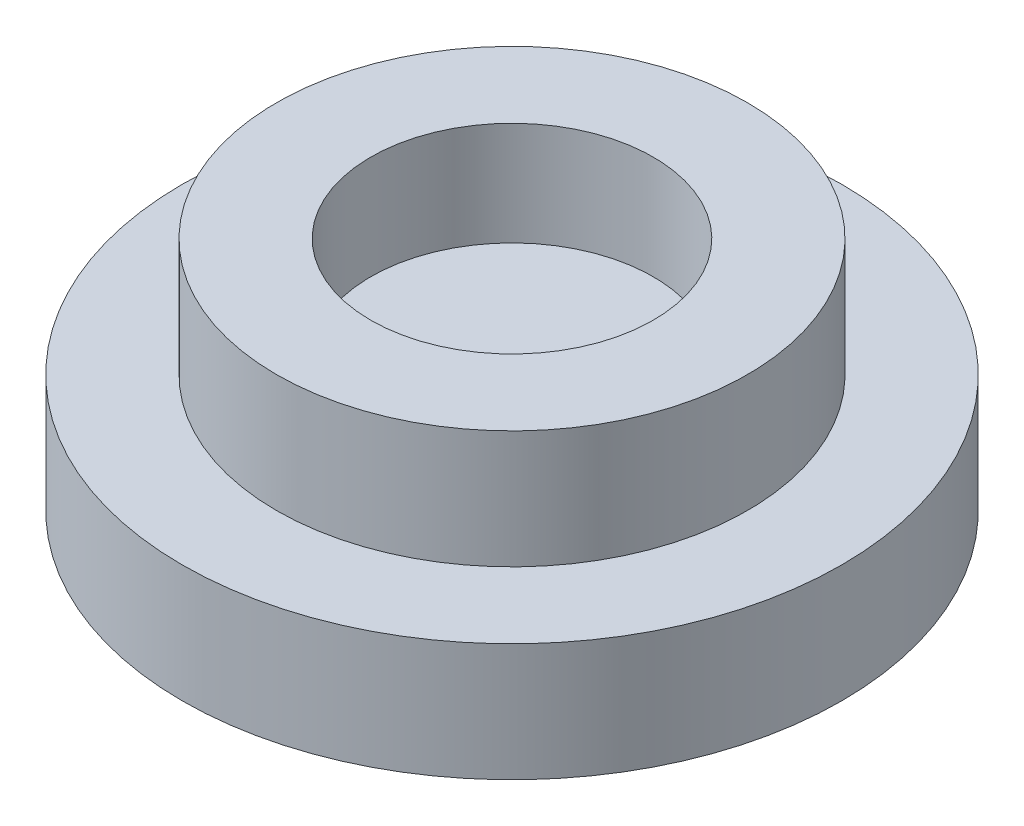
SolidWorks part; units mm, degrees
ref_plane "Front Plane" through (0, 0, 0) normal (0, 0, 1) x (1, 0, 0)
ref_plane "Top Plane" through (0, 0, 0) normal (0, 1, 0) x (1, 0, 0)
ref_plane "Right Plane" through (0, 0, 0) normal (1, 0, 0) x (0, 0, -1)
sketch "magnet_dim" plane through (0, 0, 0) normal (0, 1, 0) x (1, 0, 0)
  circle A0 centre (0, 0) radius 3
sketch "magnet_outer_dim" plane through (0, 0, 0) normal (0, 1, 0) x (1, 0, 0)
  circle A0 centre (0, 0) radius 5
sketch "motor_dim" plane through (0, 0, 0) normal (0, 1, 0) x (1, 0, 0)
  circle A0 centre (0, 0) radius 5
sketch "mototr_outer_dim" plane through (0, 0, 0) normal (0, 1, 0) x (1, 0, 0)
  circle A0 centre (0, 0) radius 7
extrude "Boss-Extrude7" add sketch "magnet_outer_dim" along normal blind 2.5
extrude "Cut-Extrude1" cut sketch "magnet_dim" along normal blind 2.2 from offset 0.3
extrude "Boss-Extrude8" add sketch "mototr_outer_dim" against normal blind 2.5
extrude "Cut-Extrude4" cut sketch "motor_dim" against normal blind 3.2 from offset 0.2
